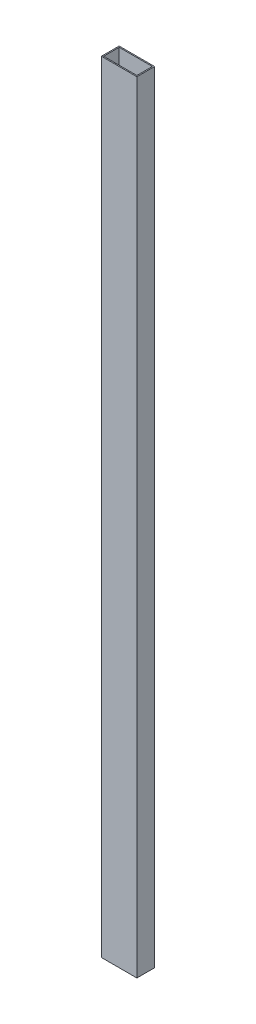
SolidWorks part; units mm, degrees
ref_plane "Front Plane" through (0, 0, 0) normal (0, 0, 1) x (1, 0, 0)
ref_plane "Top Plane" through (0, 0, 0) normal (0, 1, 0) x (1, 0, 0)
ref_plane "Right Plane" through (0, 0, 0) normal (1, 0, 0) x (0, 0, -1)
sketch "Sketch2" plane through (0, 0, 0) normal (0, 1, 0) x (1, 0, 0)
  line L0 (-1.5875, 23.8125) -> (49.2125, 23.8125)
  line L1 (0, 0) -> (47.625, 0)
  line L2 (0, 0) -> (0, 22.225)
  line L3 (0, 22.225) -> (47.625, 22.225)
  line L4 (47.625, 0) -> (47.625, 22.225)
  line L5 (49.2125, -1.5875) -> (49.2125, 23.8125)
  line L6 (-1.5875, -1.5875) -> (49.2125, -1.5875)
  line L7 (-1.5875, -1.5875) -> (-1.5875, 23.8125)
  dimension "D1" = 1.5875
  dimension "D2" = 25.4
  dimension "D3" = 50.8
extrude "Boss-Extrude1" add sketch "Sketch2" along normal blind 1117.6
